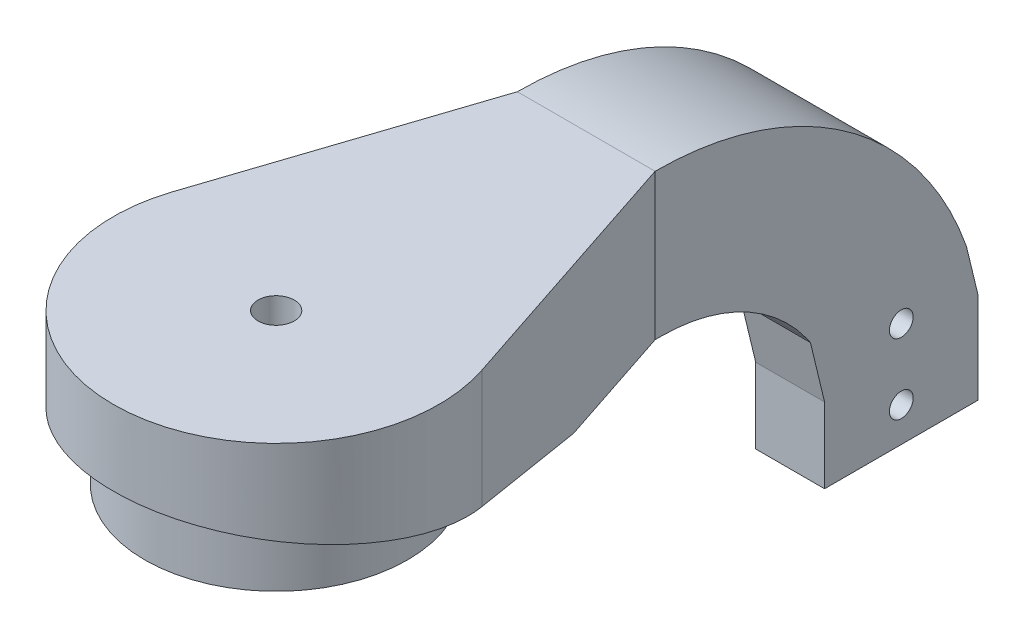
SolidWorks part; units mm, degrees
ref_plane "Alzado" through (0, 0, 0) normal (0, 0, 1) x (1, 0, 0)
ref_plane "Planta" through (0, 0, 0) normal (0, 1, 0) x (1, 0, 0)
ref_plane "Vista lateral" through (0, 0, 0) normal (1, 0, 0) x (0, 0, -1)
sketch "Croquis1" plane through (0, 0, 0) normal (0, 1, 0) x (1, 0, 0)
  circle A0 centre (0, 0) radius 21
  dimension "D1" = 42
extrude "Saliente-Extruir1" add sketch "Croquis1" along normal blind 24
sketch "Croquis2" plane through (0, 24, 0) normal (0, 1, 0) x (1, 0, 0)
  circle A0 centre (0, 0) radius 2.9
  dimension "D1" = 5.8
extrude "Cortar-Extruir1" cut sketch "Croquis2" against normal mid plane 60
sketch "Croquis3" plane through (0, 24, 0) normal (0, 1, 0) x (1, 0, 0)
  circle A0 centre (0, 0) radius 26
  dimension "D1" = 52
extrude "Saliente-Extruir2" add sketch "Croquis3" against normal blind 12
sketch "Croquis4" plane through (0, 0, 0) normal (1, 0, 0) x (0, 0, -1)
  line L0 (-26, 12) -> (30.0914, 0.6913)
  line L1 (30.0914, 0.6913) -> (30.0914, 24)
  line L2 (-26, 12) -> (-26, 13.9303)
  line L3 (-26, 24) -> (-26, 12) construction
  line L4 (-26, 24) -> (30.0914, 24)
  line L5 (26, 24) -> (-26, 24) construction
  line L6 (-26, 24) -> (-26, 12) construction
  line L7 (-26, 24) -> (-26, 12)
  dimension "D1" = 57.22
extrude "Saliente-Extruir3" add sketch "Croquis4" along normal mid plane 52 contours L4 L7 L2 L0 L1
sketch "Croquis6" plane through (26, 0, 0) normal (1, 0, 0) x (0, 0, -1)
  line L1 (30.0914, 24) -> (49.5204, 24)
  line L2 (30.0914, 24) -> (30.0914, 0.6913)
  line L3 (30.0914, 0.6913) -> (49.5204, 0.6913)
  line L4 (49.5204, 24) -> (49.5204, 0.6913)
  dimension "D1" = 19.429
extrude "Saliente-Extruir4" add sketch "Croquis6" against normal blind 52
sketch "Croquis5" plane through (0, 24, 0) normal (0, 1, 0) x (1, 0, 0)
  line L0 (-11, 49.5204) -> (11, 49.5204)
  line L1 (-26, 49.5204) -> (26, 49.5204) construction
  line L2 (11, 49.5204) -> (24.6837, 8.1679)
  line L3 (-11, 49.5204) -> (-24.6837, 8.1679)
  line L4 (11, 49.5204) -> (26, 49.5204)
  line L5 (11, 49.5204) -> (24.6837, 8.1679)
  line L6 (24.6837, 8.1679) -> (26, 49.5204)
  arc A0 (-24.6837, 8.1679) -> (24.6837, 8.1679) centre (0, 0) ccw
  point P7 (0, 49.5204)
  line M2 (-26, 49.5204) -> (-26, -26)
  line M3 (-26, -26) -> (26, -26)
  line M4 (26, -26) -> (26, 49.5204)
  line M6 (26, 49.5204) -> (-26, 49.5204)
  dimension "D1" = 52
  dimension "D2" = 22
extrude "Cortar-Extruir2" cut sketch "Croquis5" against normal through all contours L2 L6 M6 | A0 M3 M4 | A0 M2 M3 | A0 L3 M6 M2 | A0 L6 M4
sketch "Croquis7" plane through (0, 0, 0) normal (1, 0, 0) x (0, 0, -1)
  line L0 (49.5204, 0.6913) -> (57.5204, 0.6913)
  line L1 (99.2487, -11.2535) -> (73.7487, -11.2535)
  line L2 (49.5204, 0.6913) -> (49.5204, 24)
  line L3 (49.5204, 24) -> (61.5204, 24)
  line L4 (49.5204, 24) -> (148.7708, 24)
  line L6 (30.0914, 0.6913) -> (49.5204, 0.6913) construction
  arc A0 (73.7487, -11.2535) -> (50.4781, 0.6913) centre (50.4781, -27.9487) ccw
  arc A1 (99.2487, -11.2535) -> (49.5204, 24) centre (49.5204, -28.7) ccw
  dimension "D3" = 57.28
  dimension "D4" = 105.4
  dimension "D5" = 25.5
  dimension "D1" = 8
  dimension "D2" = 12
extrude "Saliente-Extruir5" add sketch "Croquis7" along normal mid plane 22
sketch "Croquis9" plane through (11, 0, 0) normal (1, 0, 0) x (0, 0, -1)
  line L0 (99.2487, -11.2535) -> (101.0946, -18.8834)
  line L1 (101.0946, -18.8834) -> (101.0946, -33.4584)
  line L2 (101.0946, -33.4584) -> (76.5946, -33.4584)
  line L3 (76.5946, -33.4584) -> (76.5946, -21.4584)
  line L4 (76.5946, -21.4584) -> (74.329, -12.0935)
  line L5 (99.2487, -11.2535) -> (73.7487, -11.2535) construction
  circle A0 centre (50.4773, -27.9492) radius 28.641
  arc A1 (73.7487, -11.2535) -> (50.4781, 0.6913) centre (50.4781, -27.9487) ccw construction
  line M6 (73.7487, -11.2535) -> (99.2487, -11.2535)
  dimension "D1" = 57.282
  dimension "D2" = 166.4
  dimension "D3" = 7.85
  dimension "D4" = 14.575
  dimension "D5" = 24.5
  dimension "D6" = 12
  dimension "D8" = 166.4
extrude "Saliente-Extruir6" add sketch "Croquis9" against normal blind 11 contours A0 L2 L1 L0 M6 | L2 A0 L4 L3
sketch "Croquis10" plane through (0, 0, 0) normal (-1, 0, 0) x (0, 0, 1)
  line L0 (-101.0946, -33.4584) -> (-76.5946, -33.4584) construction
  line L1 (-101.0946, -33.4584) -> (-76.5946, -33.4584) construction
  circle A0 centre (-88.8446, -27.9584) radius 1.9
  circle A1 centre (-88.8446, -16.7284) radius 1.9
  point P9 (-88.8446, -33.4584)
  dimension "D1" = 3.8
  dimension "D2" = 11.23
  dimension "D3" = 5.5
  dimension "D4" = 16.73
extrude "Cortar-Extruir3" cut sketch "Croquis10" against normal through all
sketch "Croquis11" plane through (0, 24, 0) normal (0, 1, 0) x (1, 0, 0)
  circle A0 centre (0, 0) radius 2.9
  dimension "D1" = 5.8
extrude "Cortar-Extruir4" cut sketch "Croquis11" against normal through all
sketch "Croquis12" plane through (0, 0, 0) normal (0, -1, 0) x (1, 0, 0)
  line L1 (2.825, 4.893) -> (-2.825, 4.893)
  line L2 (-2.825, 4.893) -> (-5.65, 0)
  line L3 (-5.65, 0) -> (-2.825, -4.893)
  line L4 (-2.825, -4.893) -> (2.825, -4.893)
  line L5 (2.825, -4.893) -> (5.65, 0)
  line L6 (5.65, 0) -> (2.825, 4.893)
  circle A0 centre (0, 0) radius 4.893 construction
  dimension "D1" = 5.65
extrude "Cortar-Extruir5" cut sketch "Croquis12" against normal blind 4
